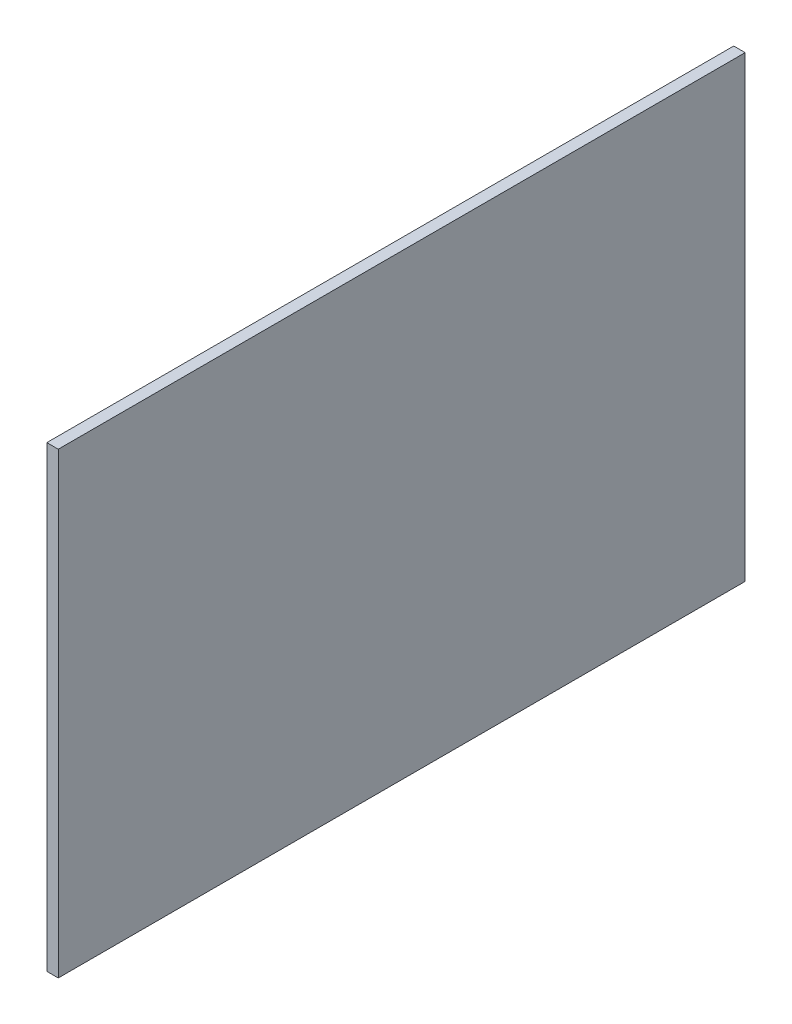
SolidWorks part; units mm, degrees
ref_plane "Front Plane" through (0, 0, 0) normal (0, 0, 1) x (1, 0, 0)
ref_plane "Top Plane" through (0, 0, 0) normal (0, 1, 0) x (1, 0, 0)
ref_plane "Right Plane" through (0, 0, 0) normal (1, 0, 0) x (0, 0, -1)
sketch "Sketch1" plane through (0, 0, 0) normal (1, 0, 0) x (0, 0, -1)
  line L1 (150, -100) -> (-150, -100)
  line L2 (150, -100) -> (150, 100)
  line L3 (150, 100) -> (-150, 100)
  line L4 (-150, -100) -> (-150, 100)
  line L5 (150, -100) -> (-150, 100) construction
  line L6 (150, 100) -> (-150, -100) construction
  point P0 (0, 0)
  dimension "D1" = 200
  dimension "D2" = 300
extrude "Boss-Extrude1" add sketch "Sketch1" along normal blind 5
sketch "Sketch2" plane through (0, 0, 0) normal (-1, 0, 0) x (0, 0, 1)
  line L0 (145, -85) -> (145, 85)
  line L1 (135, 95) -> (-135, 95)
  line L2 (-145, 85) -> (-145, -85)
  line L3 (-135, -95) -> (135, -95)
  arc A0 (135, 95) -> (145, 85) centre (135, 85) cw
  arc A1 (145, -85) -> (135, -95) centre (135, -85) cw
  arc A2 (-145, -85) -> (-135, -95) centre (-135, -85) ccw
  arc A3 (-145, 85) -> (-135, 95) centre (-135, 85) cw
  dimension "D1" = 10
extrude "Boss-Extrude2" add sketch "Sketch2" along normal blind 5
